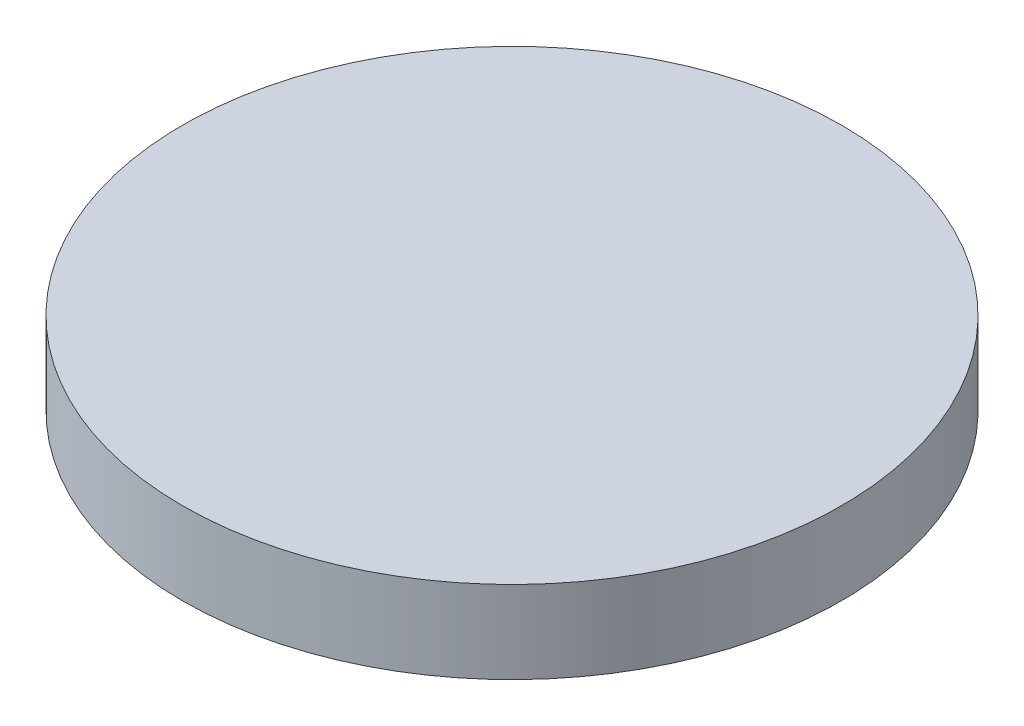
SolidWorks part; units mm, degrees
ref_plane "Alzado" through (0, 0, 0) normal (0, 0, 1) x (1, 0, 0)
ref_plane "Planta" through (0, 0, 0) normal (0, 1, 0) x (1, 0, 0)
ref_plane "Vista lateral" through (0, 0, 0) normal (1, 0, 0) x (0, 0, -1)
sketch "Croquis1" plane through (0, 0, 0) normal (0, 1, 0) x (1, 0, 0)
  circle A0 centre (0, 0) radius 40
  dimension "D1" = 80
extrude "Saliente-Extruir1" add sketch "Croquis1" along normal blind 10
